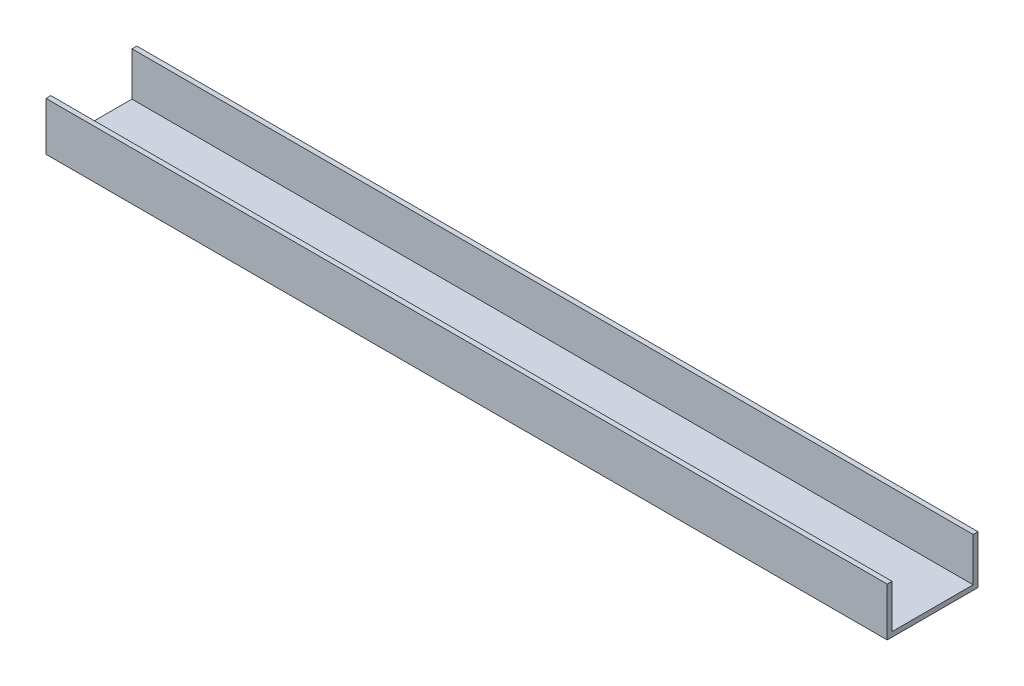
SolidWorks part; units mm, degrees
ref_plane "정면" through (0, 0, 0) normal (0, 0, 1) x (1, 0, 0)
ref_plane "윗면" through (0, 0, 0) normal (0, 1, 0) x (1, 0, 0)
ref_plane "우측면" through (0, 0, 0) normal (1, 0, 0) x (0, 0, -1)
sketch "스케치1" plane through (0, 0, 0) normal (0, 1, 0) x (1, 0, 0)
  line L1 (0, 0) -> (695, 0)
  line L2 (0, 0) -> (0, 75)
  line L3 (0, 75) -> (695, 75)
  line L4 (695, 0) -> (695, 75)
  dimension "D1" = 695
  dimension "D2" = 75
extrude "보스-돌출1" add sketch "스케치1" along normal blind 4
sketch "스케치2" plane through (0, 4, 0) normal (0, 1, 0) x (1, 0, 0)
  line L0 (695, 0) -> (695, 75) construction
  line L1 (0, 0) -> (695, 0)
  line L2 (0, 0) -> (0, 4)
  line L3 (0, 4) -> (695, 4)
  line L4 (695, 0) -> (695, 4)
  line L5 (0, 75) -> (0, 0) construction
  line L6 (695, 75) -> (0, 75)
  line L7 (695, 75) -> (695, 71)
  line L8 (695, 71) -> (0, 71)
  line L9 (0, 75) -> (0, 71)
  dimension "D1" = 4
  dimension "D2" = 4
extrude "보스-돌출2" add sketch "스케치2" along normal blind 36
